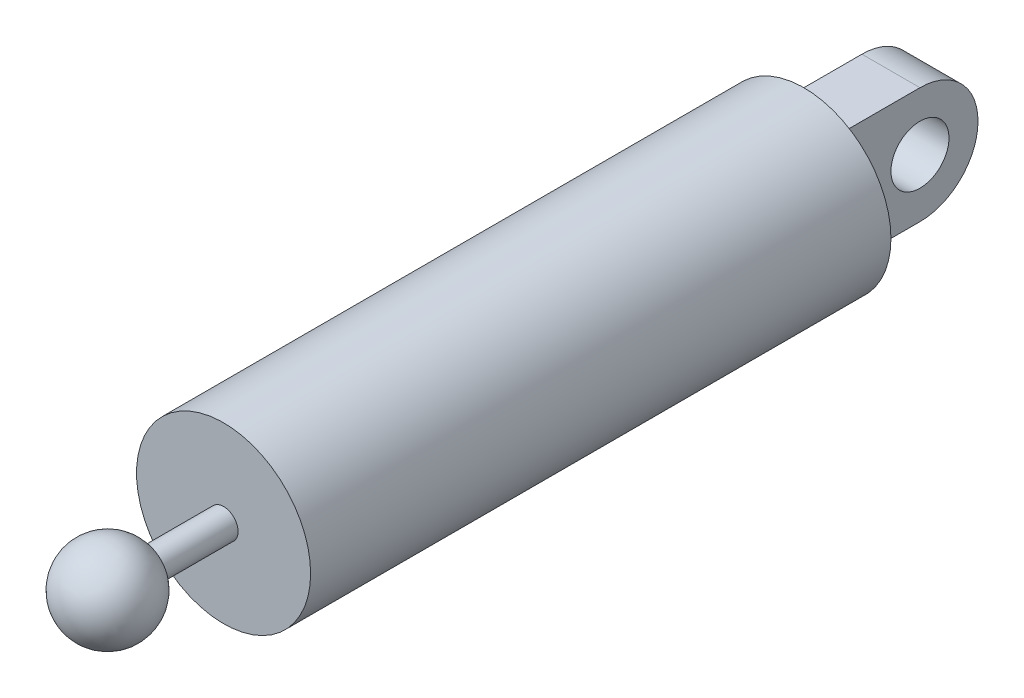
SolidWorks part; units mm, degrees
ref_plane "Alzado" through (0, 0, 0) normal (0, 0, 1) x (1, 0, 0)
ref_plane "Planta" through (0, 0, 0) normal (0, 1, 0) x (1, 0, 0)
ref_plane "Vista lateral" through (0, 0, 0) normal (1, 0, 0) x (0, 0, -1)
sketch "Croquis1" plane through (0, 0, 0) normal (0, 0, 1) x (1, 0, 0)
  circle A0 centre (0, 0) radius 7.5
  dimension "D1" = 15
extrude "Saliente-Extruir1" add sketch "Croquis1" along normal blind 50
sketch "Croquis4" plane through (0, 0, 0) normal (0, 0, -1) x (-1, 0, 0)
  line L0 (0, 8.25) -> (0, -8.25) construction
  line L1 (2.5, 5) -> (-2.5, 5)
  line L2 (2.5, 5) -> (2.5, -5)
  line L3 (2.5, -5) -> (-2.5, -5)
  line L4 (-2.5, 5) -> (-2.5, -5)
  line L5 (2.5, 5) -> (-2.5, -5) construction
  line L6 (2.5, -5) -> (-2.5, 5) construction
  point P0 (0, 0)
  dimension "D1" = 5
  dimension "D2" = 10
extrude "Saliente-Extruir2" add sketch "Croquis4" along normal blind 12.5
sketch "Croquis5" plane through (-2.5, 0, 0) normal (-1, 0, 0) x (0, 0, 1)
  line L0 (-12.5, 5) -> (0, 5) construction
  line L1 (-12.5, -5) -> (-12.5, 5) construction
  line L2 (-12.5, -5) -> (0, -5) construction
  circle A0 centre (-7.5, 0) radius 2.5
  arc A1 (-7.5, 5) -> (-7.5, -5) centre (-7.5, 0) ccw
  line M2 (0, 5) -> (-12.5, 5)
  line M3 (-12.5, 5) -> (-12.5, -5)
  line M4 (-12.5, -5) -> (0, -5)
  dimension "D2" = 5
  dimension "D3" = 5
  dimension "D1" = 5
extrude "Cortar-Extruir1" cut sketch "Croquis5" against normal blind 5 contours A1 M3 M4 | A1 M2 M3 | A0
sketch "Croquis6" plane through (0, 0, 50) normal (0, 0, 1) x (1, 0, 0)
  circle A0 centre (0, 0) radius 1.25
  point P3 (0, 0)
  dimension "D1" = 2.5
extrude "Saliente-Extruir3" add sketch "Croquis6" along normal blind 10
sketch "Croquis7" plane through (0, 0, 60) normal (0, 0, 1) x (1, 0, 0)
  line L0 (0, 7.5) -> (0, -7.5) construction
  line L1 (0, -8.25) -> (0, 8.25) construction
  line L2 (0, 3.75) -> (0, -3.75)
  arc A0 (0, -3.75) -> (0, 3.75) centre (0, 0) ccw
  point P8 (-6.5678, 4.2651)
  point P9 (0, 0)
  dimension "D1" = 7.5
  dimension "D2" = 15
revolve "Revolución7" add sketch "Croquis7" angle 360 about L0
